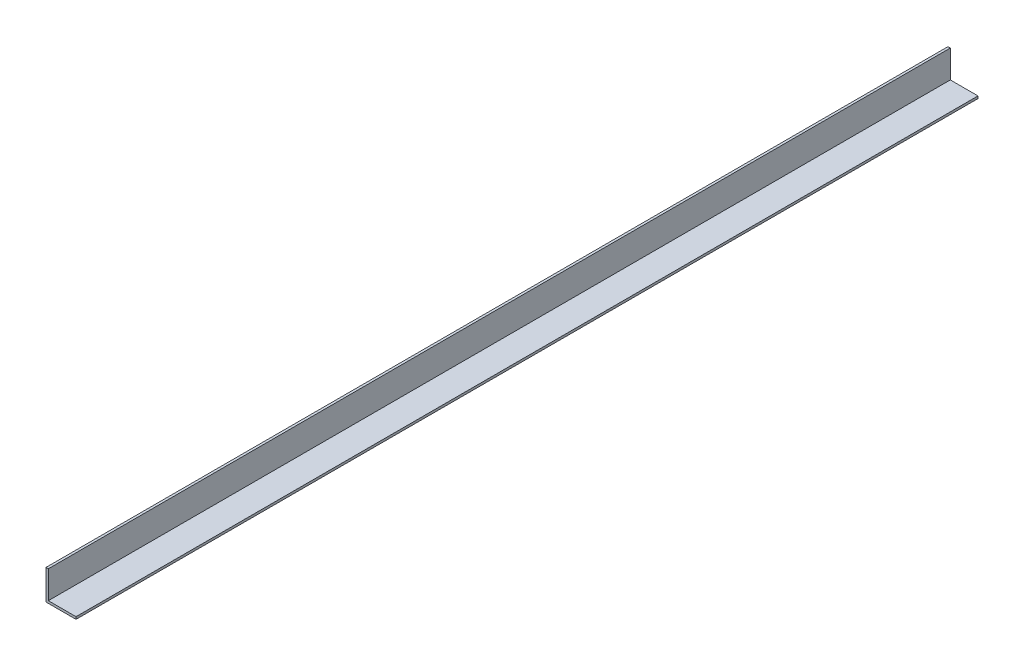
SolidWorks part; units mm, degrees
material "ASTM A36 Acero"
ref_plane "Alzado" through (0, 0, 0) normal (0, 0, 1) x (1, 0, 0)
ref_plane "Planta" through (0, 0, 0) normal (0, 1, 0) x (1, 0, 0)
ref_plane "Vista lateral" through (0, 0, 0) normal (1, 0, 0) x (0, 0, -1)
sketch "Croquis1" plane through (0, 0, 0) normal (0, 0, 1) x (1, 0, 0)
  line L0 (0, 203) -> (0, 0)
  line L1 (0, 0) -> (203, 0)
  line L2 (203, 0) -> (203, 15.88)
  line L3 (203, 15.88) -> (15.88, 15.88)
  line L4 (15.88, 15.88) -> (15.88, 203)
  line L5 (15.88, 203) -> (0, 203)
  dimension "D1" = 15.88
  dimension "D2" = 203
extrude "Saliente-Extruir1" add sketch "Croquis1" against normal blind 6100
